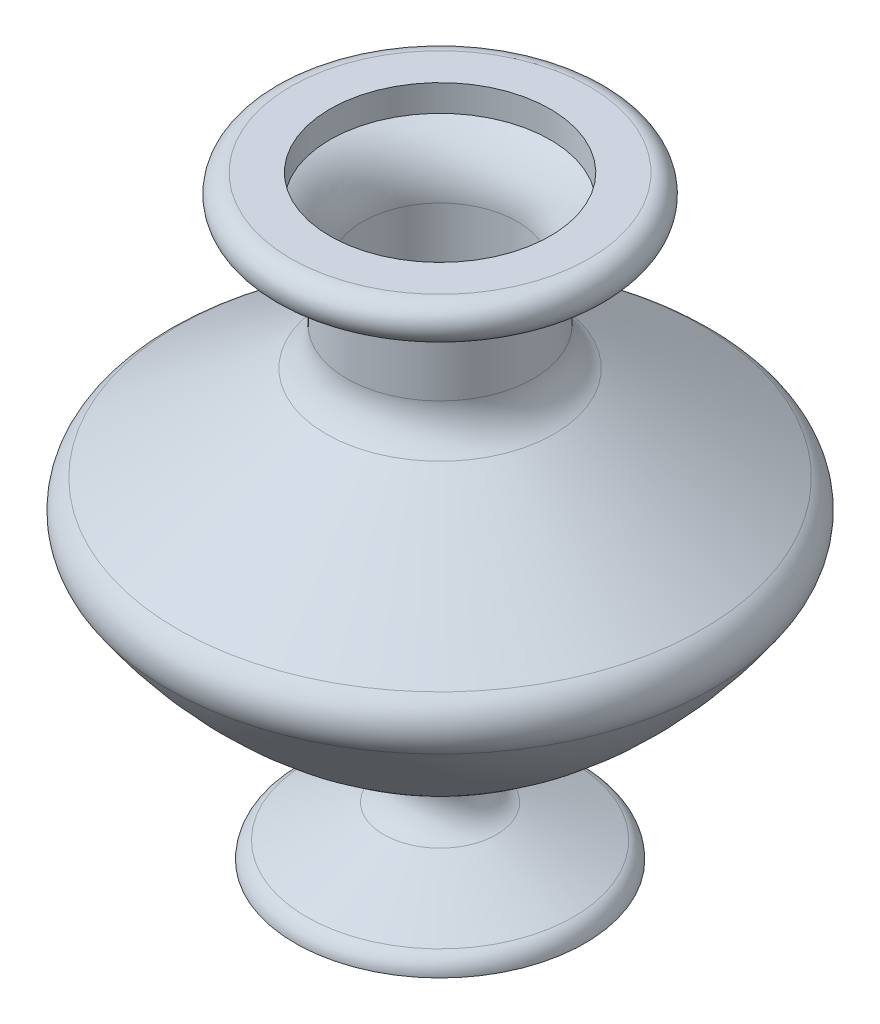
SolidWorks part; units mm, degrees
ref_plane "Front Plane" through (0, 0, 0) normal (0, 0, 1) x (1, 0, 0)
ref_plane "Top Plane" through (0, 0, 0) normal (0, 1, 0) x (1, 0, 0)
ref_plane "Right Plane" through (0, 0, 0) normal (1, 0, 0) x (0, 0, -1)
sketch "Sketch1" plane through (0, 0, 0) normal (0, 0, 1) x (1, 0, 0)
  line L0 (0, 80) -> (0, -80) construction
  line L1 (0, -80) -> (-38.9051, -80)
  line L2 (-35.8588, -75.382) -> (-15.1334, -66.5845)
  line L3 (0, -45.9) -> (-73.1937, -3.6416) construction
  line L4 (-70.5774, 8.9884) -> (-30.6515, 34.449)
  line L5 (-25.1036, 44.5668) -> (-25.1036, 58.2668)
  line L6 (-40.1036, 80) -> (-29.6036, 80)
  line L7 (-29.6036, 72.8514) -> (-29.6036, 80)
  line L8 (-20.7036, 44.5668) -> (-20.7036, 58.2668)
  line L9 (-68.2116, 5.2785) -> (-28.2857, 30.7391)
  line L10 (-24.44, -75.315) -> (-13.4142, -70.6347)
  line L11 (0, -75.6) -> (-24.5079, -75.6)
  line L12 (0, -75.6) -> (0, -80)
  line L13 (-29.6036, 72.8514) -> (-31.3782, 68.8129) construction
  line L14 (-40.1036, 75.6) -> (-29.6036, 75.6) construction
  line L15 (-25.1114, -75.6) -> (-13.4142, -70.6347) construction
  line L16 (0, -75.6) -> (-25.1114, -75.6) construction
  arc A0 (-38.9051, -80) -> (-35.8588, -75.382) centre (-33.9052, -79.9846) cw
  arc A1 (-15.1334, -66.5845) -> (-15.365, -49.9209) centre (-18.65, -58.3) ccw
  arc A2 (-73.1937, -3.6416) -> (-15.365, -49.9209) centre (30.1871, 66.2688) ccw
  arc A3 (-73.1937, -3.6416) -> (-70.5774, 8.9884) centre (-65.7383, 1.4) cw
  arc A4 (-30.6515, 34.449) -> (-25.1036, 44.5668) centre (-37.1036, 44.5668) ccw
  arc A5 (-25.1036, 58.2668) -> (-39.2212, 70.0785) centre (-37.1036, 58.2668) ccw
  arc A6 (-39.2212, 70.0785) -> (-40.1036, 80) centre (-40.1036, 75) cw
  arc A7 (-24.5079, -75.6) -> (-24.44, -75.315) centre (-24.3389, -75.4897) cw
  arc A8 (-20.7036, 58.2668) -> (-29.6036, 72.8514) centre (-37.1036, 58.2668) ccw
  arc A9 (-28.2857, 30.7391) -> (-20.7036, 44.5668) centre (-37.1036, 44.5668) ccw
  arc A10 (-69.5488, -1.1768) -> (-68.2116, 5.2785) centre (-65.7383, 1.4) cw
  arc A11 (-69.5488, -1.1768) -> (-13.759, -45.8245) centre (30.1871, 66.2688) ccw
  arc A12 (-13.4142, -70.6347) -> (-13.759, -45.8245) centre (-18.65, -58.3) ccw
  arc A14 (-20.7036, 58.2668) -> (-39.9977, 74.4094) centre (-37.1036, 58.2668) ccw construction
  arc A15 (-39.9977, 74.4094) -> (-40.1036, 75.6) centre (-40.1036, 75) cw construction
  arc A16 (-25.1114, -75.6) -> (-25.1114, -75.6) centre (-25.1114, -75.6) cw construction
  point P3 (0, 0)
  point P20 (-34.8536, 80)
  point P24 (-25.1036, 51.4168)
  point P25 (-19.4526, -80)
  point P28 (-24.5079, -75.6)
  point P53 (0, 0)
  point P54 (-24.3389, -75.4897)
  point P60 (-24.44, -75.315)
  dimension "D2" = 9
  dimension "D4" = 5
  dimension "D5" = 124.8
  dimension "D8" = 9
  dimension "D12" = 12
  dimension "D13" = 12
  dimension "D14" = 5
  dimension "D1" = 160
  dimension "D3" = 18.65
  dimension "D6" = 34.1
  dimension "D7" = 60
  dimension "D9" = 21.7
  dimension "D10" = 59.7
  dimension "D11" = 13.7
  dimension "D15" = 10.5
  dimension "D17" = 8.9
  dimension "D16" = 4.4
  dimension "D18" = 4.4
  dimension "D19" = 4.4
  dimension "D20" = 4.4
revolve "Revolve1" add sketch "Sketch1" angle 360 about L0
